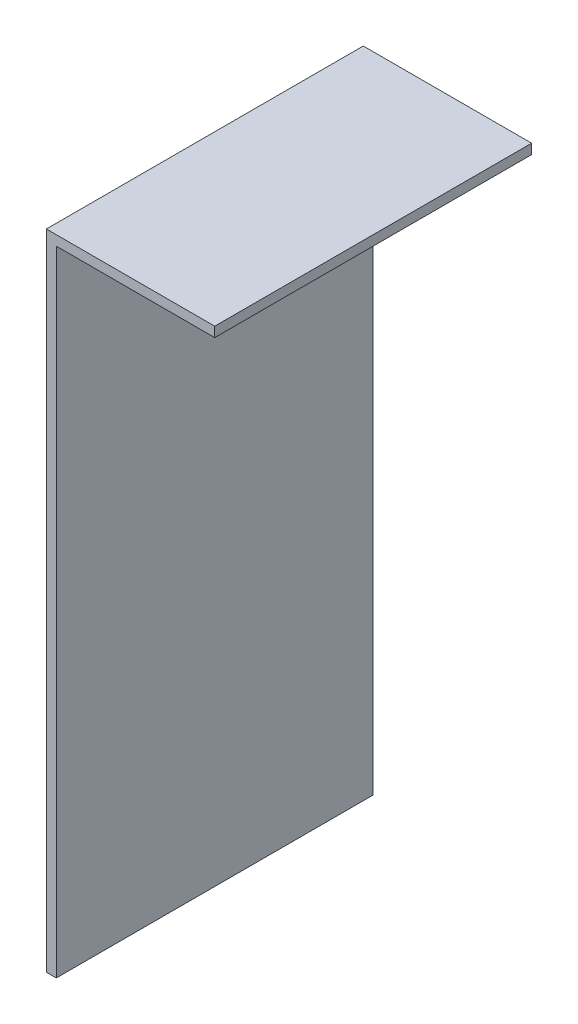
SolidWorks part; units mm, degrees
material "Glass"
ref_plane "Front Plane" through (0, 0, 0) normal (0, 0, 1) x (1, 0, 0)
ref_plane "Top Plane" through (0, 0, 0) normal (0, 1, 0) x (1, 0, 0)
ref_plane "Right Plane" through (0, 0, 0) normal (1, 0, 0) x (0, 0, -1)
sketch "Sketch1" plane through (0, 0, 0) normal (0, 0, 1) x (1, 0, 0)
  line L1 (0, 0) -> (53.975, 0)
  line L2 (0, 0) -> (0, 206.375)
  line L3 (0, 206.375) -> (53.975, 206.375)
  line L4 (53.975, 0) -> (53.975, 206.375)
  line L5 (3.175, 0) -> (53.975, 0)
  line L6 (3.175, 0) -> (3.175, 203.2)
  line L7 (3.175, 203.2) -> (53.975, 203.2)
  line L8 (53.975, 0) -> (53.975, 203.2)
  dimension "D1" = 50.8
  dimension "D2" = 203.2
  dimension "D3" = 0
  dimension "D4" = 0
  dimension "D5" = 3.175
  dimension "D6" = 3.175
extrude "Boss-Extrude1" add sketch "Sketch1" along normal blind 101.6 contours L8 L1 L4 L3 L2 L6 L7
